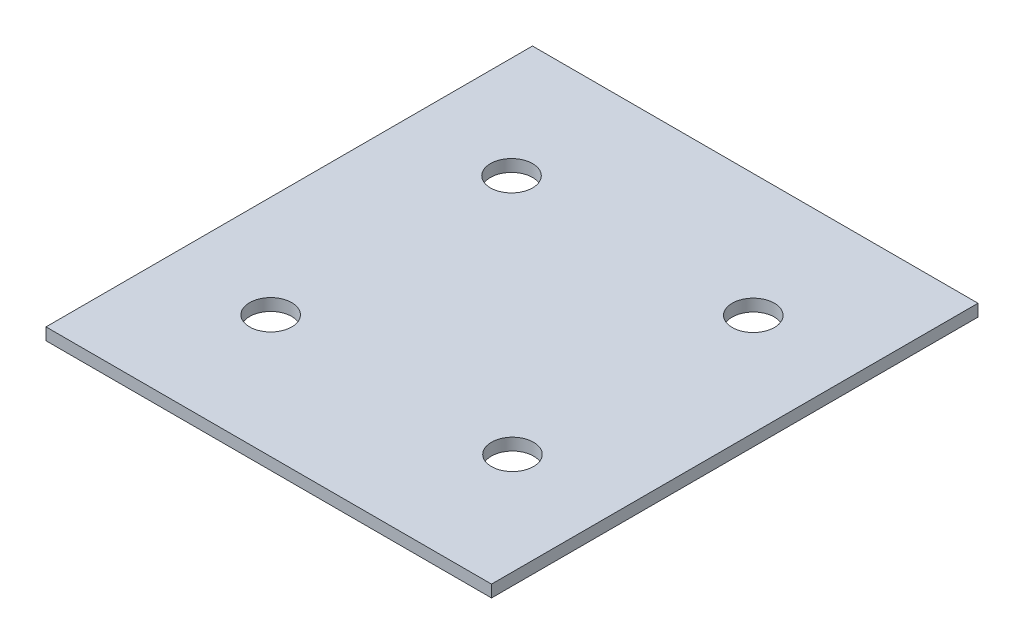
SolidWorks part; units mm, degrees
ref_plane "Front Plane" through (0, 0, 0) normal (0, 0, 1) x (1, 0, 0)
ref_plane "Top Plane" through (0, 0, 0) normal (0, 1, 0) x (1, 0, 0)
ref_plane "Right Plane" through (0, 0, 0) normal (1, 0, 0) x (0, 0, -1)
sketch "Sketch1" plane through (0, 0, 0) normal (0, 0, 1) x (1, 0, 0)
  line L0 (0, 3.175) -> (0, -3.175) construction
  line L1 (-117.475, 3.175) -> (117.475, 3.175)
  line L2 (-117.475, 3.175) -> (-117.475, -3.175)
  line L3 (-117.475, -3.175) -> (117.475, -3.175)
  line L4 (117.475, 3.175) -> (117.475, -3.175)
  dimension "D1" = 6.35
  dimension "D2" = 234.95
extrude "Boss-Extrude1" add sketch "Sketch1" along normal up to surface (256.54 mm away)
sketch "Sketch2" plane through (0, -3.175, 0) normal (0, -1, 0) x (1, 0, 0)
  circle A0 centre (-63.754, 191.77) radius 11.1125 construction
  circle A1 centre (-63.754, 191.77) radius 11.1125
  circle A2 centre (-63.754, 64.77) radius 11.1125 construction
  circle A3 centre (63.754, 64.77) radius 11.1125 construction
  circle A4 centre (63.754, 191.77) radius 11.1125 construction
  circle A5 centre (-63.754, 64.77) radius 11.1125
  circle A6 centre (63.754, 64.77) radius 11.1125
  circle A7 centre (63.754, 191.77) radius 11.1125
extrude "Cut-Extrude1" cut sketch "Sketch2" against normal up to next
